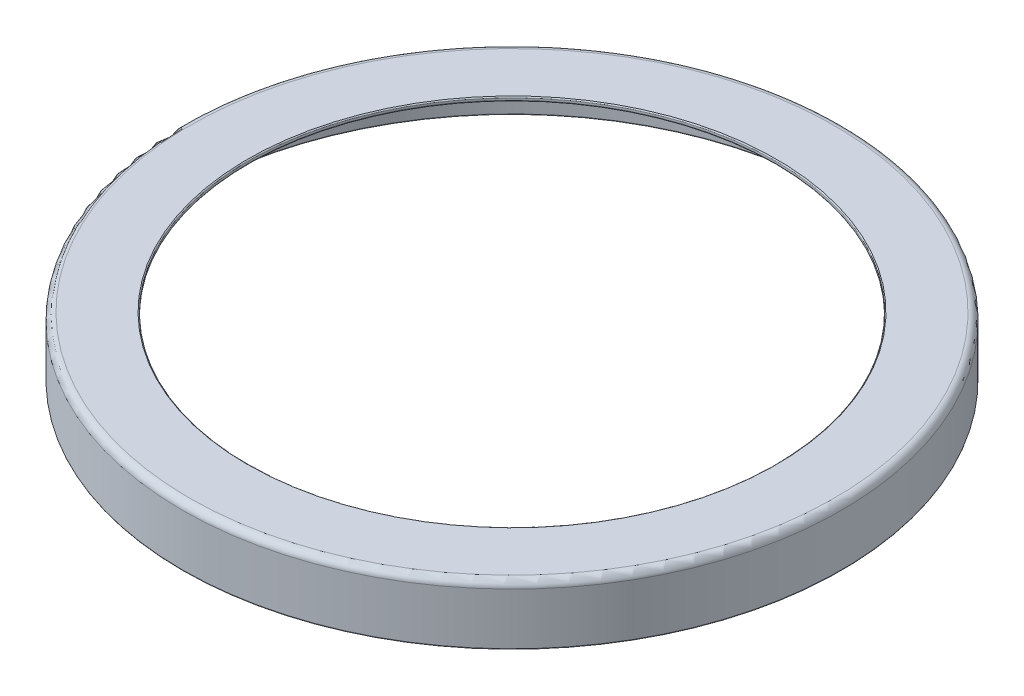
SolidWorks part; units mm, degrees
ref_plane "Plano frontal" through (0, 0, 0) normal (0, 0, 1) x (1, 0, 0)
ref_plane "Plano superior" through (0, 0, 0) normal (0, 1, 0) x (1, 0, 0)
ref_plane "Plano direito" through (0, 0, 0) normal (1, 0, 0) x (0, 0, -1)
sketch "Esboço1" plane through (0, 0, 0) normal (0, 0, 1) x (1, 0, 0)
  line L0 (0, -73.0426) -> (0, 79.259) construction
  line L1 (65.15, 28.5715) -> (65.15, 29.5715)
  line L2 (65.15, 29.5715) -> (81.5, 29.5715)
  line L3 (81.5, 29.5715) -> (81.5, 14.8215)
  line L4 (81.5, 14.8215) -> (80.5, 14.8215)
  line L5 (80.5, 14.8215) -> (80.5, 28.5715)
  line L6 (80.5, 28.5715) -> (65.15, 28.5715)
  dimension "D1" = 1
  dimension "D2" = 1
  dimension "D3" = 65.15
  dimension "D4" = 81.5
  dimension "D5" = 14.75
revolve "Revolução1" add sketch "Esboço1" angle 360 about L0
fillet "Filete1" radius 1.75 1 edges at (0, 29.5715, -81.5)
fillet "Filete2" radius 0.5 1 edges at (0, 28.5715, -80.5)
fillet "Filete4" radius 0.25 4 edges at (0, 14.8215, -81.5) (0, 14.8215, -80.5) (0, 28.5715, -65.15) (0, 29.5715, -65.15)
